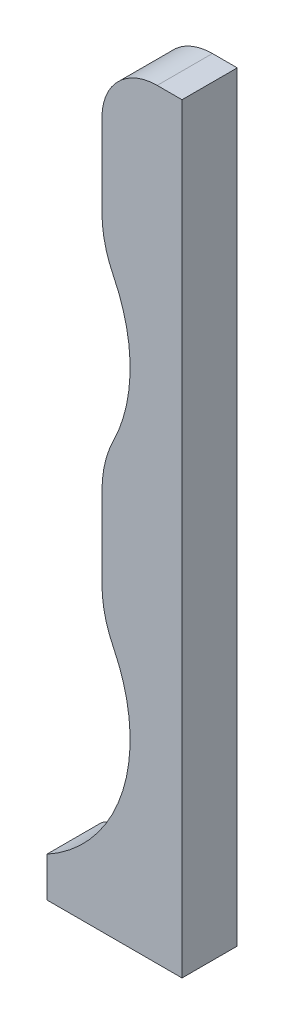
SolidWorks part; units mm, degrees
ref_plane "Front Plane" through (0, 0, 0) normal (0, 0, 1) x (1, 0, 0)
ref_plane "Top Plane" through (0, 0, 0) normal (0, 1, 0) x (1, 0, 0)
ref_plane "Right Plane" through (0, 0, 0) normal (1, 0, 0) x (0, 0, -1)
sketch "Sketch1" plane through (0, 0, 0) normal (0, 0, 1) x (1, 0, 0)
  line L0 (3170.2152, 2687.5612) -> (3170.2152, 2643.8319)
  line L1 (3170.2152, 2687.5612) -> (3168.788, 2687.5612)
  line L2 (3170.2152, 2643.8319) -> (3162.438, 2643.8319)
  line L3 (3162.438, 2643.8319) -> (3162.438, 2646.1053)
  line L4 (3165.613, 2661.1301) -> (3165.613, 2665.7974)
  line L5 (3165.613, 2679.634) -> (3165.613, 2684.3862)
  arc A0 (3162.438, 2646.1053) -> (3166.2714, 2658.3143) centre (3157.9788, 2654.2118) ccw
  arc A1 (3165.613, 2661.1301) -> (3166.2714, 2658.3143) centre (3171.963, 2661.1301) ccw
  arc A2 (3166.2714, 2668.6131) -> (3166.2714, 2676.8182) centre (3157.9788, 2672.7157) ccw
  arc A3 (3165.613, 2679.634) -> (3166.2714, 2676.8182) centre (3171.963, 2679.634) ccw
  arc A4 (3166.2714, 2668.6131) -> (3165.613, 2665.7974) centre (3171.963, 2665.7974) ccw
  arc A5 (3168.788, 2687.5612) -> (3165.613, 2684.3862) centre (3168.788, 2684.3862) ccw
extrude "Boss-Extrude1" add sketch "Sketch1" along normal blind 3.175
